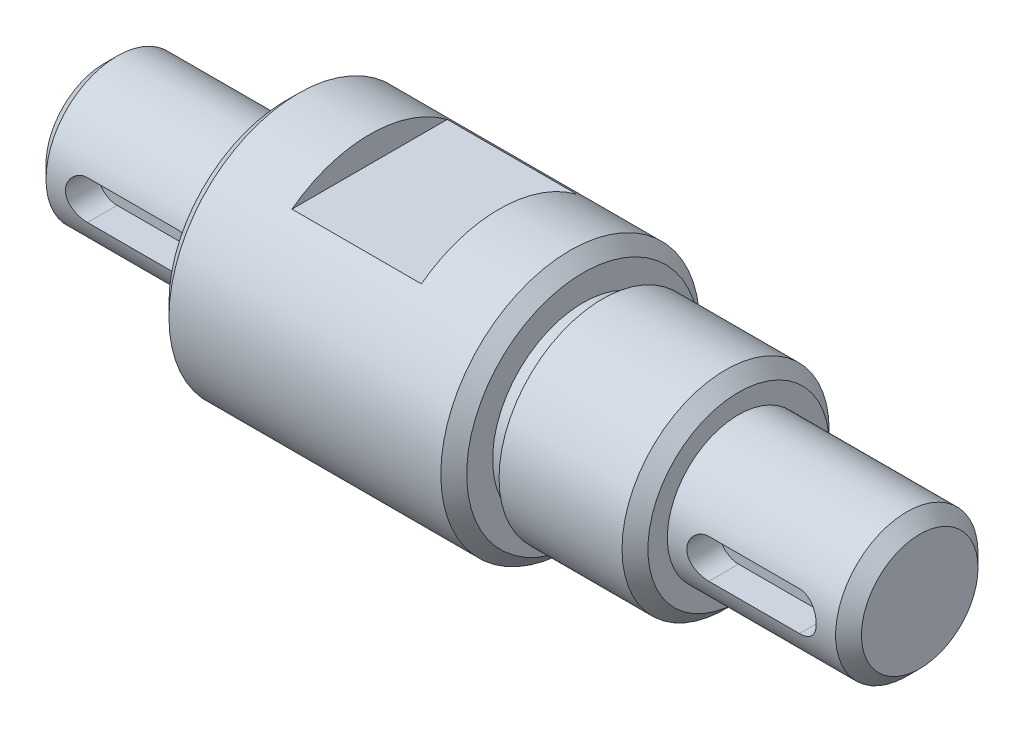
SolidWorks part; units mm, degrees
material "Plain Carbon Steel"
ref_plane "Front Plane" through (0, 0, 0) normal (0, 0, 1) x (1, 0, 0)
ref_plane "Top Plane" through (0, 0, 0) normal (0, 1, 0) x (1, 0, 0)
ref_plane "Right Plane" through (0, 0, 0) normal (1, 0, 0) x (0, 0, -1)
sketch "Sketch1" plane through (0, 0, 0) normal (1, 0, 0) x (0, 0, -1)
  circle A0 centre (0, 0) radius 20
  dimension "D1" = 40
extrude "Boss-Extrude1" add sketch "Sketch1" along normal blind 126
sketch "Sketch2" plane through (0, 0, 0) normal (-1, 0, 0) x (0, 0, 1)
  circle A0 centre (0, 0) radius 11
  dimension "D1" = 22
extrude "Cut-Extrude1" cut sketch "Sketch2" against normal blind 28 flip side to cut
sketch "Sketch3" plane through (126, 0, 0) normal (1, 0, 0) x (0, 0, -1)
  circle A0 centre (0, 0) radius 11
  dimension "D1" = 22
extrude "Cut-Extrude2" cut sketch "Sketch3" against normal blind 28 flip side to cut
sketch "Sketch4" plane through (98, 0, 0) normal (1, 0, 0) x (0, 0, -1)
  circle A0 centre (0, 0) radius 16
  dimension "D1" = 32
extrude "Cut-Extrude3" cut sketch "Sketch4" against normal blind 21 flip side to cut
sketch "Sketch5" plane through (77, 0, 0) normal (1, 0, 0) x (0, 0, -1)
  circle A0 centre (0, 0) radius 14
  dimension "D1" = 28
extrude "Cut-Extrude4" cut sketch "Sketch5" against normal blind 3 flip side to cut
chamfer "Chamfer1" distance 2 angle 45 5 edges at (126, 0, -11) (98, 0, -16) (74, 0, -20) (28, 0, 20) (0, 0, 11)
sketch "Sketch6" plane through (0, 0, 0) normal (0, 0, 1) x (1, 0, 0)
  line L0 (41, 16) -> (61, 16)
  line L1 (61, 16) -> (61, 22)
  line L2 (61, 22) -> (41, 22)
  line L3 (41, 22) -> (41, 16)
  dimension "D1" = 41
  dimension "D2" = 20
  dimension "D3" = 16
  dimension "D4" = 6
extrude "Cut-Extrude5" cut sketch "Sketch6" against normal through all and the other way through all
ref_plane "Plane1" through (0, 0, 11) normal (0, 0, 1) x (1, 0, 0)
sketch "Sketch7" plane through (0, 0, 11) normal (0, 0, 1) x (1, 0, 0)
  line L0 (8, 3) -> (22, 3)
  line L1 (22, -3) -> (8, -3)
  line L2 (8, 0) -> (22, 0) construction
  line L3 (104, 3) -> (118, 3)
  line L4 (118, -3) -> (104, -3)
  line L5 (104, 0) -> (118, 0) construction
  arc A0 (22, -3) -> (22, 3) centre (22, 0) ccw
  arc A1 (8, 3) -> (8, -3) centre (8, 0) ccw
  arc A2 (118, -3) -> (118, 3) centre (118, 0) ccw
  arc A3 (104, 3) -> (104, -3) centre (104, 0) ccw
  point P6 (5, 0)
  point P7 (25, 0)
  point P15 (101, 0)
  point P16 (121, 0)
  dimension "D1" = 6
  dimension "D2" = 20
  dimension "D3" = 5
  dimension "D4" = 6
  dimension "D5" = 20
  dimension "D6" = 121
extrude "Cut-Extrude6" cut sketch "Sketch7" against normal blind 5
